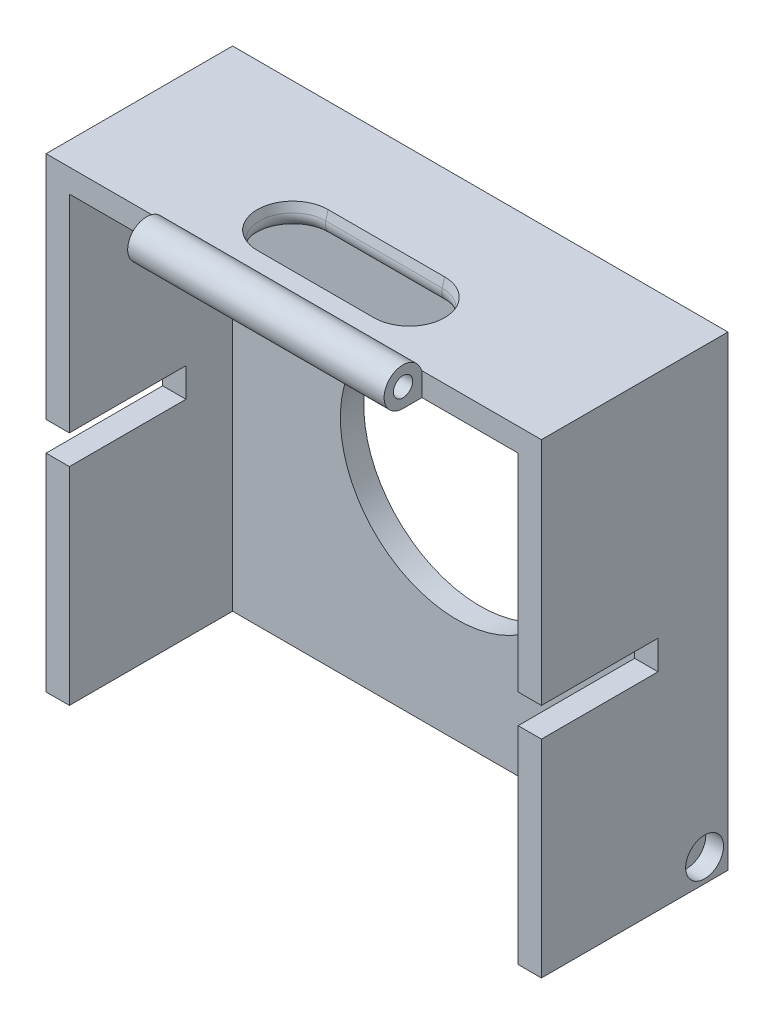
SolidWorks part; units mm, degrees
ref_plane "Front Plane" through (0, 0, 0) normal (0, 0, 1) x (1, 0, 0)
ref_plane "Top Plane" through (0, 0, 0) normal (0, 1, 0) x (1, 0, 0)
ref_plane "Right Plane" through (0, 0, 0) normal (1, 0, 0) x (0, 0, -1)
sketch "Sketch1" plane through (0, 0, 0) normal (0, 0, 1) x (1, 0, 0)
  line L1 (-19.25, 19) -> (19.25, 19)
  line L2 (-19.25, 19) -> (-19.25, -19)
  line L3 (-19.25, -19) -> (19.25, -19)
  line L4 (19.25, 19) -> (19.25, -19)
  line L5 (-19.25, 19) -> (19.25, -19) construction
  line L6 (-19.25, -19) -> (19.25, 19) construction
  circle A0 centre (0, 0) radius 10
  point P0 (0, 0)
  dimension "D3" = 20
  dimension "D1" = 38.5
  dimension "D2" = 38
extrude "Boss-Extrude1" add sketch "Sketch1" along normal blind 2
sketch "Sketch2" plane through (0, 0, 2) normal (0, 0, 1) x (1, 0, 0)
  line L0 (-19.25, -19) -> (-21.25, -19)
  line L1 (-21.25, -19) -> (-21.25, 21)
  line L2 (-21.25, 21) -> (21.25, 21)
  line L4 (19.25, -19) -> (21.25, -19)
  line L6 (19.25, -19) -> (19.25, 19)
  line L7 (19.25, 19) -> (-19.25, 19)
  line L8 (0, 40.5) -> (0, -19) construction
  line L9 (-19.25, 19) -> (-19.25, -19)
  line L10 (-19.25, -19) -> (19.25, -19) construction
  line L11 (-19.25, -19) -> (19.25, -19)
  line L12 (19.25, -19) -> (19.25, 19)
  line L13 (19.25, 19) -> (-19.25, 19)
  line L14 (-19.25, 19) -> (-19.25, -19)
  line L15 (-19.25, -19) -> (19.25, -19)
  line L16 (21.25, -19) -> (21.25, 21)
  point P10 (0, 21)
  dimension "D1" = 0
  dimension "D2" = 2
  dimension "D3" = 2
extrude "Boss-Extrude2" add sketch "Sketch2" along normal blind 14 and the other way up to surface (2 mm away) other way up to face at (10, 0, 0)
sketch "Sketch3" plane through (-19.25, 0, 0) normal (1, 0, 0) x (0, 0, -1)
  line L0 (-2, 0) -> (-16, 0) construction
  line L1 (-2, 19) -> (-2, -19) construction
  line L2 (-16, 19) -> (-16, -19) construction
  line L3 (-16, 1.25) -> (-9, 0) construction
  line L4 (-6, 1.25) -> (-16, 1.25)
  line L5 (-6, 1.25) -> (-6, -1.25)
  line L6 (-6, -1.25) -> (-16, -1.25)
  line L7 (-16, 1.25) -> (-16, -1.25)
  line L8 (-9, 0) -> (-16, -1.25) construction
  dimension "D1" = 2.5
  dimension "D2" = 4
extrude "Cut-Extrude1" cut sketch "Sketch3" against normal up to next
ref_plane "Plane1" through (0, 0, 0) normal (1, 0, 0) x (0, 0, -1)
mirror "Mirror1" about plane through (0, 0, 0) normal (1, 0, 0) of "Cut-Extrude1"
sketch "Sketch5" plane through (0, 19, 0) normal (0, -1, 0) x (1, 0, 0)
  line L0 (-5, 11.091) -> (5, 11.091) construction
  line L1 (0, -51757.809) -> (0, 51777.035) construction
  line L2 (-5, 13.591) -> (5, 13.591)
  line L3 (-5, 8.591) -> (5, 8.591)
  arc A0 (-5, 13.591) -> (-5, 8.591) centre (-5, 11.091) ccw
  arc A1 (5, 8.591) -> (5, 13.591) centre (5, 11.091) ccw
  circle A2 centre (0, 11.091) radius 1.218 construction
  point P4 (0, 11.091)
  dimension "D1" = 10
  dimension "D2" = 5
extrude "Cut-Extrude2" cut sketch "Sketch5" against normal through all draft 15 draft outward yes
fillet "Fillet1" radius 1 4 edges at (-7.5, 19, 11.091) (0, 19, 13.591) (7.5, 19, 11.091) (0, 19, 8.591)
sketch "Sketch7" plane through (0, 0, 0) normal (1, 0, 0) x (0, 0, -1)
  line L2 (-16, 19) -> (-22.1271, 19) construction
  line L3 (-16, 1.25) -> (-16, 21) construction
  line L4 (0, 21) -> (-16, 21) construction
  line L5 (-17.625, 19) -> (-16, 19)
  line L6 (-16, 19) -> (-16, 21)
  circle A0 centre (-17.625, 20.625) radius 0.825
  arc A1 (-16.1425, 21.2904) -> (-17.625, 19) centre (-17.625, 20.625) ccw
  arc A2 (-16, 21) -> (-16.1425, 21.2904) centre (-11.8288, 23.2267) cw
  dimension "D1" = 1.65
  dimension "D2" = 3.25
  dimension "D3" = 2
  dimension "D4" = 1.625
extrude "Boss-Extrude3" add sketch "Sketch7" along normal blind 11 and the other way blind 11
sketch "Sketch8" plane through (21.25, 0, 0) normal (1, 0, 0) x (0, 0, -1)
  line L0 (0, 21) -> (0, -19) construction
  line L1 (0, -19) -> (-16, -19) construction
  circle A0 centre (-2, -17) radius 1.625
  dimension "D1" = 3.25
  dimension "D2" = 2
  dimension "D3" = 2
extrude "Cut-Extrude3" cut sketch "Sketch8" against normal blind 1.524
mirror "Mirror2" about plane through (0, 0, 0) normal (1, 0, 0) of "Cut-Extrude3"
